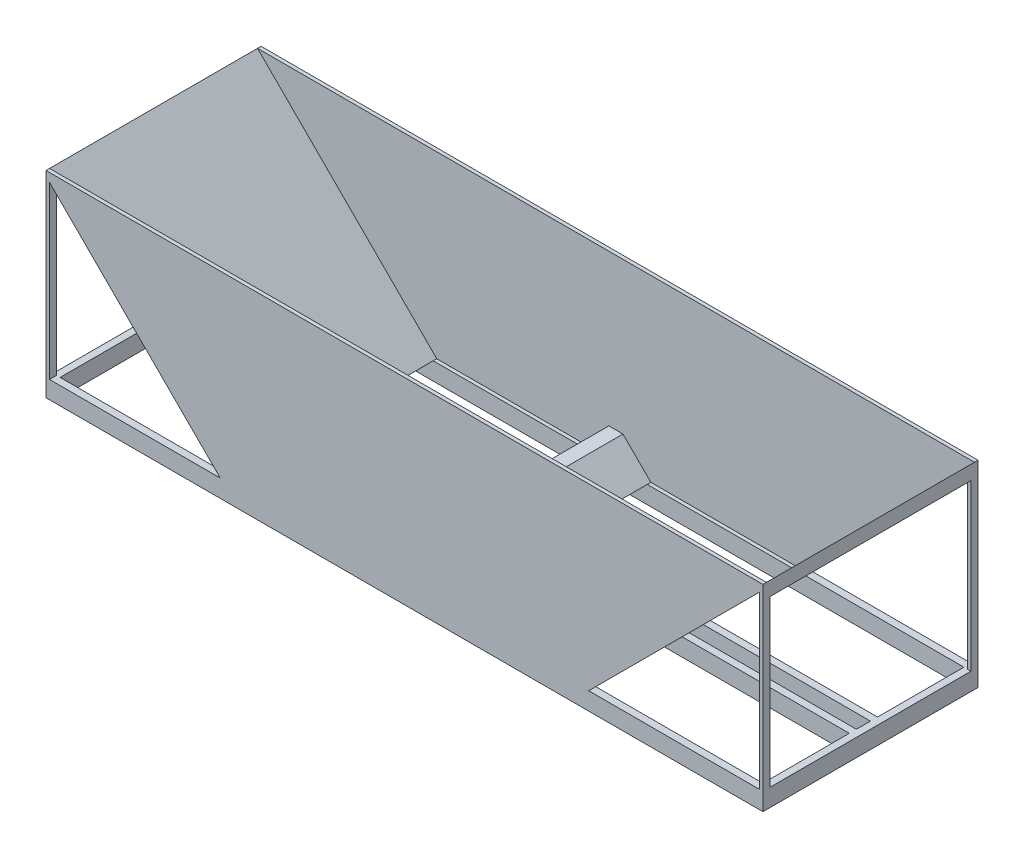
SolidWorks part; units mm, degrees
ref_plane "Front Plane" through (0, 0, 0) normal (0, 0, 1) x (1, 0, 0)
ref_plane "Top Plane" through (0, 0, 0) normal (0, 1, 0) x (1, 0, 0)
ref_plane "Right Plane" through (0, 0, 0) normal (1, 0, 0) x (0, 0, -1)
sketch "Sketch1" plane through (0, 0, 0) normal (0, 1, 0) x (1, 0, 0)
  line L1 (-508, 152.4) -> (508, 152.4)
  line L2 (-508, 152.4) -> (-508, -152.4)
  line L3 (-508, -152.4) -> (508, -152.4)
  line L4 (508, 152.4) -> (508, -152.4)
  line L5 (-498, 142.4) -> (498, 142.4)
  line L6 (-498, 142.4) -> (-498, -142.4)
  line L7 (-498, -142.4) -> (498, -142.4)
  line L8 (498, 142.4) -> (498, -142.4)
  point P9 (508, 0)
  dimension "D1" = 1016
  dimension "D2" = 304.8
  dimension "D3" = 152.4
  dimension "D4" = 508
  dimension "D5" = 10
  dimension "D6" = 10
  dimension "D7" = 10
  dimension "D8" = 10
extrude "Boss-Extrude1" add sketch "Sketch1" along normal blind 10 and the other way blind 15
sketch "Sketch2" plane through (0, 0, 0) normal (0, 1, 0) x (1, 0, 0)
  line L0 (-498, 142.4) -> (-498, -142.4) construction
  line L1 (-498, 20) -> (-30, 20)
  line L2 (-498, 20) -> (-498, 10)
  line L3 (-498, 10) -> (-10, 10)
  line L4 (498, 20) -> (498, 10)
  line L5 (498, -142.4) -> (498, 142.4) construction
  line L6 (498, 142.4) -> (-498, 142.4) construction
  line L7 (-498, -10) -> (-10, -10)
  line L8 (-498, -10) -> (-498, -20)
  line L9 (30, -20) -> (498, -20)
  line L10 (498, -10) -> (498, -20)
  line L11 (-20, 142.4) -> (-10, 142.4)
  line L12 (-20, 142.4) -> (-20, 30)
  line L13 (-20, -142.4) -> (-10, -142.4)
  line L14 (-10, 142.4) -> (-10, 20)
  line L15 (-498, -142.4) -> (498, -142.4) construction
  line L16 (-20, -30) -> (-20, -142.4)
  line L17 (10, 142.4) -> (20, 142.4)
  line L18 (10, 142.4) -> (10, 20)
  line L19 (10, -142.4) -> (20, -142.4)
  line L20 (20, 142.4) -> (20, 30)
  line L21 (-10, -20) -> (-10, -142.4)
  line L22 (10, -20) -> (10, -142.4)
  line L23 (20, -30) -> (20, -142.4)
  line L24 (-498, -20) -> (-30, -20)
  line L27 (10, -10) -> (498, -10)
  line L28 (10, 10) -> (498, 10)
  line L29 (-10, -10) -> (-10, -20)
  line L30 (10, -10) -> (10, -20)
  line L31 (-10, 20) -> (-10, 10)
  line L32 (10, 20) -> (10, 10)
  line L34 (30, 20) -> (498, 20)
  arc A0 (20, -30) -> (30, -20) centre (30, -30) cw
  arc A1 (-20, -30) -> (-30, -20) centre (-30, -30) ccw
  arc A2 (20, 30) -> (30, 20) centre (30, 30) ccw
  arc A3 (-20, 30) -> (-30, 20) centre (-30, 30) cw
  point P37 (-20, -20)
  point P44 (20, 20)
  dimension "D2" = 10
  dimension "D9" = 10
  dimension "D10" = 10
  dimension "D1" = 10
  dimension "D3" = 20
  dimension "D4" = 10
  dimension "D5" = 10
  dimension "D6" = 10
  dimension "D7" = 20
  dimension "D8" = 10
extrude "Boss-Extrude2" add sketch "Sketch2" along normal blind 10 and the other way blind 15
sketch "Sketch3" plane through (0, 0, 0) normal (0, 0, 1) x (1, 0, 0)
  line L0 (-508, 10) -> (-508, 264)
  line L1 (-508, 264) -> (-254, 10)
  line L2 (-508, 10) -> (508, 10) construction
  line L3 (-508, 10) -> (-503, 10)
  line L4 (0, 289.7) -> (0, -86.1151) construction
  line L8 (-503, 251.9289) -> (-503, 10)
  line L9 (-503, 251.9289) -> (-261.0711, 10)
  line L10 (-261.0711, 10) -> (-254, 10)
  line L11 (261.0711, 10) -> (254, 10)
  line L12 (503, 251.9289) -> (261.0711, 10)
  line L13 (503, 251.9289) -> (503, 10)
  line L14 (508, 10) -> (503, 10)
  line L15 (508, 264) -> (254, 10)
  line L16 (508, 10) -> (508, 264)
  dimension "D1" = 45
  dimension "D2" = 254
  dimension "D3" = 5
  dimension "D4" = 5
extrude "Boss-Extrude3" add sketch "Sketch3" along normal blind 152.4 and the other way blind 152.4
sketch "Sketch4" plane through (0, 10, 0) normal (0, 1, 0) x (1, 0, 0)
  line L0 (-30, 20) -> (-254, 20) construction
  line L1 (-253.9496, 20) -> (253.0996, 20)
  line L2 (-253.9496, 20) -> (-253.9496, -20)
  line L3 (-253.9496, -20) -> (253.0996, -20)
  line L4 (253.0996, 20) -> (253.0996, -20)
  line L5 (30, -20) -> (254, -20) construction
extrude "Boss-Extrude7" add sketch "Sketch4" along normal blind 5
sketch "Sketch5" plane through (508, 0, 0) normal (1, 0, 0) x (0, 0, -1)
  line L0 (-152.4, -15) -> (-152.4, 264) construction
  line L1 (-142.4, 244) -> (142.4, 244)
  line L2 (-142.4, 244) -> (-142.4, 10)
  line L3 (-142.4, 10) -> (142.4, 10)
  line L4 (142.4, 244) -> (142.4, 10)
  line L5 (152.4, -15) -> (152.4, 264) construction
  line L6 (152.4, 264) -> (-152.4, 264) construction
  line L7 (-152.4, -15) -> (152.4, -15) construction
  dimension "D1" = 10
  dimension "D2" = 10
  dimension "D3" = 20
  dimension "D4" = 25
extrude "Cut-Extrude1" cut sketch "Sketch5" against normal blind 15
sketch "Sketch6" plane through (-508, 0, 0) normal (-1, 0, 0) x (0, 0, 1)
  line L0 (-152.4, 264) -> (152.4, 264) construction
  line L1 (-142.4, 244) -> (142.4, 244)
  line L2 (-142.4, 244) -> (-142.4, 10)
  line L3 (-142.4, 10) -> (142.4, 10)
  line L4 (142.4, 244) -> (142.4, 10)
  line L5 (-152.4, -15) -> (-152.4, 264) construction
  line L6 (152.4, -15) -> (152.4, 264) construction
  line L7 (-152.4, -15) -> (152.4, -15) construction
  dimension "D1" = 20
  dimension "D2" = 10
  dimension "D3" = 10
  dimension "D4" = 25
extrude "Cut-Extrude2" cut sketch "Sketch6" against normal blind 15
sketch "Sketch7" plane through (0, 0, -152.4) normal (0, 0, -1) x (-1, 0, 0)
  line L0 (-49.3858, 10) -> (-9.8479, 49.5379)
  line L1 (-9.8479, 49.5379) -> (10.1521, 49.5379)
  line L2 (10.1521, 49.5379) -> (49.69, 10)
  line L3 (-49.3858, 10) -> (49.69, 10)
  line L6 (-254, 10) -> (254, 10) construction
  point P2 (0, 0)
  point P5 (0, 0)
  point P9 (0, 0)
  point P10 (0, 0)
  dimension "D1" = 45
  dimension "D2" = 45
  dimension "D3" = 20
  dimension "D4" = 49.69
extrude "Boss-Extrude8" add sketch "Sketch7" against normal blind 304.8
sketch "Sketch8" plane through (0, 0, 152.4) normal (0, 0, 1) x (1, 0, 0)
  line L0 (-508, 264) -> (508, 264)
  line L1 (508, 264) -> (254, 10)
  line L2 (254, 10) -> (-254, 10)
  line L3 (-254, 10) -> (-508, 264)
extrude "Boss-Extrude9" add sketch "Sketch8" against normal blind 5
sketch "Sketch9" plane through (0, 0, -152.4) normal (0, 0, -1) x (-1, 0, 0)
  line L0 (-508, 264) -> (508, 264)
  line L1 (508, 264) -> (254, 10)
  line L2 (254, 10) -> (-254, 10)
  line L3 (-254, 10) -> (-508, 264)
extrude "Boss-Extrude10" add sketch "Sketch9" against normal blind 5
